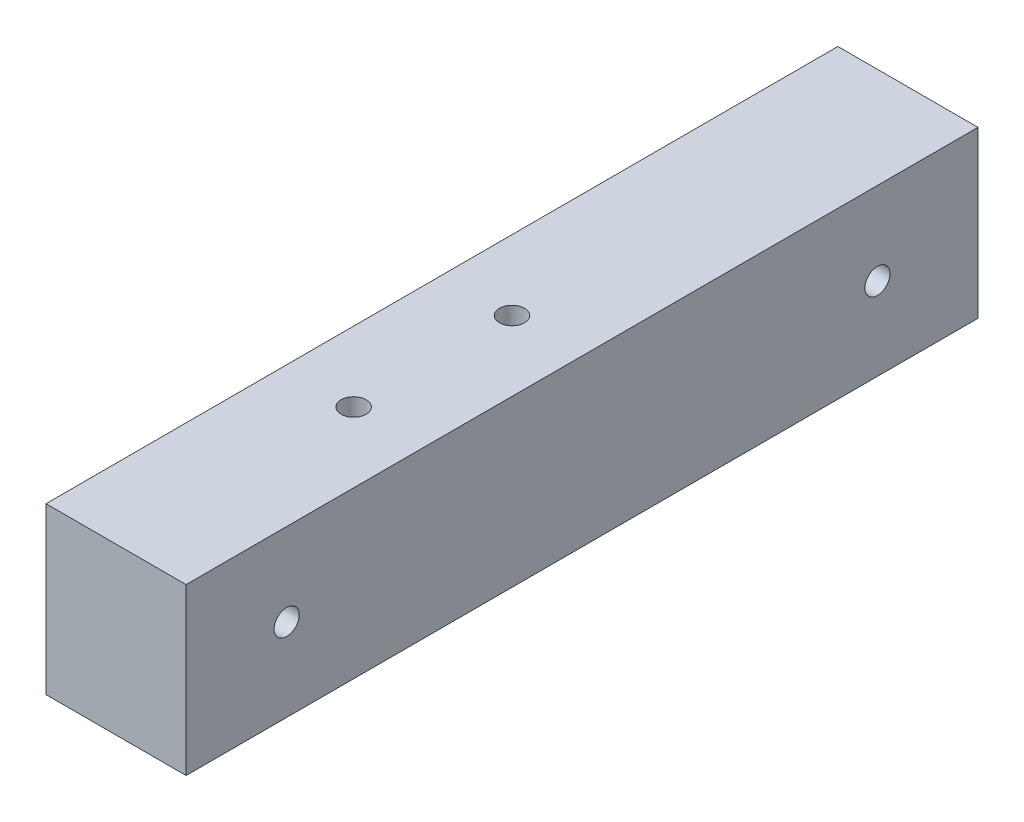
SolidWorks part; units mm, degrees
material "Pine"
ref_plane "Front Plane" through (0, 0, 0) normal (0, 0, 1) x (1, 0, 0)
ref_plane "Top Plane" through (0, 0, 0) normal (0, 1, 0) x (1, 0, 0)
ref_plane "Right Plane" through (0, 0, 0) normal (1, 0, 0) x (0, 0, -1)
sketch "Sketch1" plane through (0, 0, 0) normal (0, 0, 1) x (1, 0, 0)
  line L1 (0, 0) -> (17.69, 0)
  line L2 (0, 0) -> (0, 20.88)
  line L3 (0, 20.88) -> (17.69, 20.88)
  line L4 (17.69, 0) -> (17.69, 20.88)
  dimension "D1" = 17.69
  dimension "D2" = 20.88
extrude "Boss-Extrude1" add sketch "Sketch1" along normal blind 100
sketch "Sketch2" plane through (0, 20.88, 0) normal (0, 1, 0) x (1, 0, 0)
  line L0 (17.69, 0) -> (0, 0) construction
  line L1 (0, -100) -> (0, 0) construction
  circle A0 centre (8.845, -50) radius 1.5875
  circle A1 centre (8.845, -70) radius 1.5875
  point P0 (8.845, 0)
  point P1 (0, -50)
  point P4 (8.845, -50)
  point P11 (0, 0)
  dimension "D1" = 3.175
  dimension "D2" = 3.175
  dimension "D3" = 20
extrude "Cut-Extrude1" cut sketch "Sketch2" against normal blind 106.78
sketch "Sketch3" plane through (17.69, 0, 0) normal (1, 0, 0) x (0, 0, -1)
  line L0 (-100, 0) -> (-100, 20.88) construction
  line L1 (0, 0) -> (0, 20.88) construction
  line L2 (-100, 20.88) -> (0, 20.88) construction
  circle A0 centre (-87.3, 10.44) radius 1.5875
  circle A1 centre (-12.7, 10.44) radius 1.5875
  point P0 (-100, 20.88)
  point P1 (-100, 0)
  point P3 (-100, 10.44)
  point P5 (-87.3, 10.44)
  point P8 (-12.7, 10.44)
  point P9 (-48.4125, 20.88)
  point P10 (-48.4125, 0)
  dimension "D1" = 3.175
  dimension "D2" = 3.175
  dimension "D3" = 12.7
  dimension "D4" = 12.7
  dimension "D5" = 10.44
  dimension "D6" = 10.44
extrude "Cut-Extrude2" cut sketch "Sketch3" against normal blind 100
